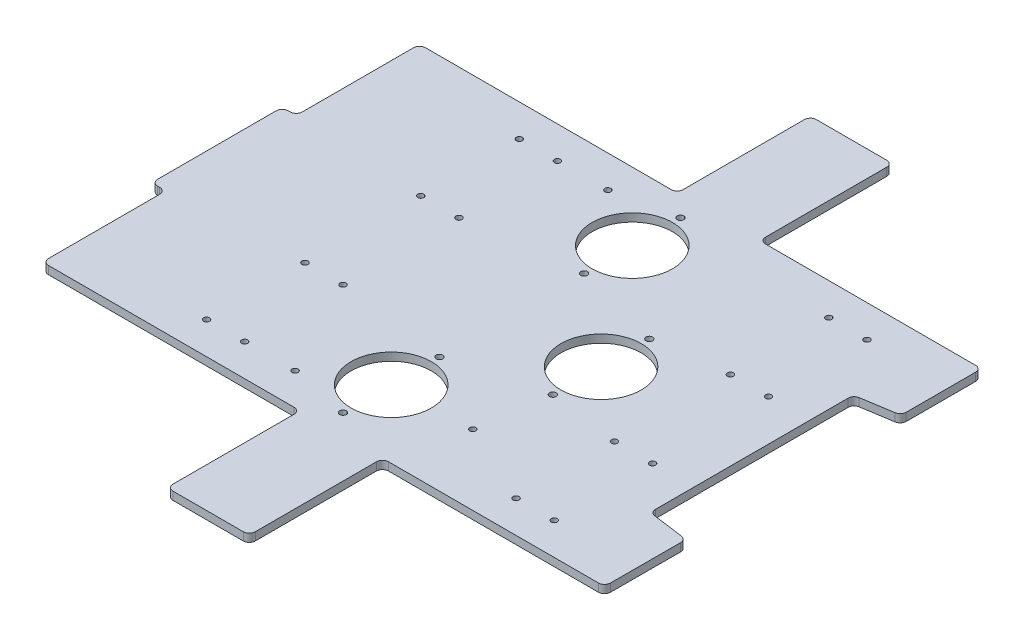
SolidWorks part; units mm, degrees
ref_plane "Front Plane" through (0, 0, 0) normal (0, 0, 1) x (1, 0, 0)
ref_plane "Top Plane" through (0, 0, 0) normal (0, 1, 0) x (1, 0, 0)
ref_plane "Right Plane" through (0, 0, 0) normal (1, 0, 0) x (0, 0, -1)
sketch "Sketch1" plane through (0, 0, 0) normal (0, 1, 0) x (1, 0, 0)
  line L4 (187.6801, 0) -> (-187.9931, 0) construction
  line L13 (92.4587, 93.85) -> (92.4587, 53.8038)
  line L14 (92.4587, 53.8038) -> (71.9148, 50.55)
  line L15 (92.5282, -53.3294) -> (71.9148, -50.55)
  line L16 (92.4587, -93.85) -> (92.5282, -53.3294)
  line L17 (71.9148, 50.55) -> (71.9148, -50.55)
  line L18 (-59.0413, 93.85) -> (-59.0413, 160.15)
  line L19 (-59.0413, 160.15) -> (-18.0413, 160.15)
  line L20 (-18.0413, 160.15) -> (-18.0413, 93.85)
  line L21 (-59.0413, 93.85) -> (-187.2913, 93.85)
  line L22 (-18.0413, 93.85) -> (92.4587, 93.85)
  line L23 (-18.0413, -93.85) -> (92.4587, -93.85)
  line L24 (-18.0413, -160.15) -> (-18.0413, -93.85)
  line L25 (-59.0413, -160.15) -> (-18.0413, -160.15)
  line L26 (-59.0413, -93.85) -> (-59.0413, -160.15)
  line L27 (-59.0413, -93.85) -> (-187.2913, -93.85)
  line L31 (-187.2913, 93.85) -> (-187.2913, 34.2746)
  line L32 (-187.2913, 34.2746) -> (-187.2913, 32.5)
  line L33 (-194.2913, -32.5) -> (-194.2913, 32.5)
  line L34 (-194.2913, 32.5) -> (-187.2913, 32.5)
  line L35 (-194.2913, -32.5) -> (-187.2913, -32.5)
  line L36 (-187.2913, -32.5) -> (-187.2913, -93.85)
  circle A0 centre (-47.5413, 60) radius 20
  circle A1 centre (-3.0852, 0) radius 20
  circle A2 centre (-47.5413, -60) radius 20
  circle A3 centre (-77.5413, 77.85) radius 1.5
  circle A4 centre (-121.6213, 28.85) radius 1.5
  circle A5 centre (-102.6513, 28.85) radius 1.5
  circle A6 centre (-121.6213, -28.85) radius 1.5
  circle A7 centre (-102.6513, -28.85) radius 1.5
  circle A8 centre (-77.5413, -77.85) radius 1.5
  circle A10 centre (32.4587, 77.85) radius 1.5
  circle A11 centre (-8.0852, -58.85) radius 1.5
  circle A12 centre (32.4587, -77.85) radius 1.5
  circle A14 centre (-121.6213, -77.85) radius 1.5
  circle A15 centre (-102.6513, -77.85) radius 1.5
  circle A16 centre (51.4287, -77.85) radius 1.5
  circle A17 centre (32.4448, -28.85) radius 1.5
  circle A18 centre (51.4148, -28.85) radius 1.5
  circle A19 centre (-121.6213, 77.85) radius 1.5
  circle A20 centre (-102.6513, 77.85) radius 1.5
  circle A21 centre (51.4148, 28.85) radius 1.5
  circle A22 centre (32.4448, 28.85) radius 1.5
  circle A23 centre (51.4287, 77.85) radius 1.5
  circle A24 centre (-47.5413, -84) radius 1.65
  circle A25 centre (-47.5413, -36) radius 1.65
  circle A26 centre (-3.0852, -24) radius 1.65
  circle A27 centre (-3.0852, 24) radius 1.65
  circle A28 centre (-47.5413, 36) radius 1.65
  circle A29 centre (-47.5413, 84) radius 1.65
  point P37 (-194.2913, 0)
  dimension "D12" = 40
  dimension "D13" = 40
  dimension "D14" = 100.15
  dimension "D16" = 75
  dimension "D17" = 93.85
  dimension "D18" = 3
  dimension "D19" = 16
  dimension "D20" = 187.7
  dimension "D21" = 16
  dimension "D22" = 65
  dimension "D23" = 194.2913
  dimension "D24" = 60.0274
  dimension "D25" = 16
  dimension "D26" = 60
  dimension "D27" = 35
  dimension "D28" = 80
  dimension "D30" = 18.97
  dimension "D31" = 65
  dimension "D32" = 65.67
  dimension "D33" = 3
  dimension "D34" = 3
  dimension "D35" = 3
  dimension "D36" = 109.75
  dimension "D37" = 3
  dimension "D40" = 3
  dimension "D41" = 3
  dimension "D44" = 49
  dimension "D45" = 18.97
  dimension "D46" = 91.64
  dimension "D47" = 3
  dimension "D48" = 3
  dimension "D49" = 3
  dimension "D50" = 16
  dimension "D52" = 20.5
  dimension "D53" = 3.3
  dimension "D54" = 3.3
  dimension "D55" = 3.3
  dimension "D56" = 3.3
  dimension "D57" = 3.3
  dimension "D58" = 3.3
  dimension "D43" = 18.97
  dimension "D3" = 20.8
  dimension "D4" = 99
  dimension "D5" = 101.1
  dimension "D6" = 20.8
  dimension "D7" = 66.3
  dimension "D8" = 41
  dimension "D9" = 110.5
  dimension "D10" = 32.5
  dimension "D11" = 7
  dimension "D15" = 128.25
  dimension "D29" = 139.75
  dimension "D38" = 49
  dimension "D39" = 49
  dimension "D42" = 18.97
extrude "Boss-Extrude2" add sketch "Sketch1" along normal blind 4
fillet "Fillet1" radius 3 20 edges at (-187.2913, 2, -93.85) (-194.2913, 2, -32.5) (-187.2913, 2, -32.5) (-194.2913, 2, 32.5) (-187.2913, 2, 32.5) (-187.2913, 2, 93.85) (-59.0413, 2, 93.85) (-59.0413, 2, 160.15) (-18.0413, 2, 160.15) (-18.0413, 2, 93.85) (92.4587, 2, 93.85) (92.5282, 2, 53.3294) (71.9148, 2, 50.55) (71.9148, 2, -50.55) (92.4587, 2, -53.8038) (92.4587, 2, -93.85) (-59.0413, 2, -93.85) (-18.0413, 2, -93.85) (-18.0413, 2, -160.15) (-59.0413, 2, -160.15)
